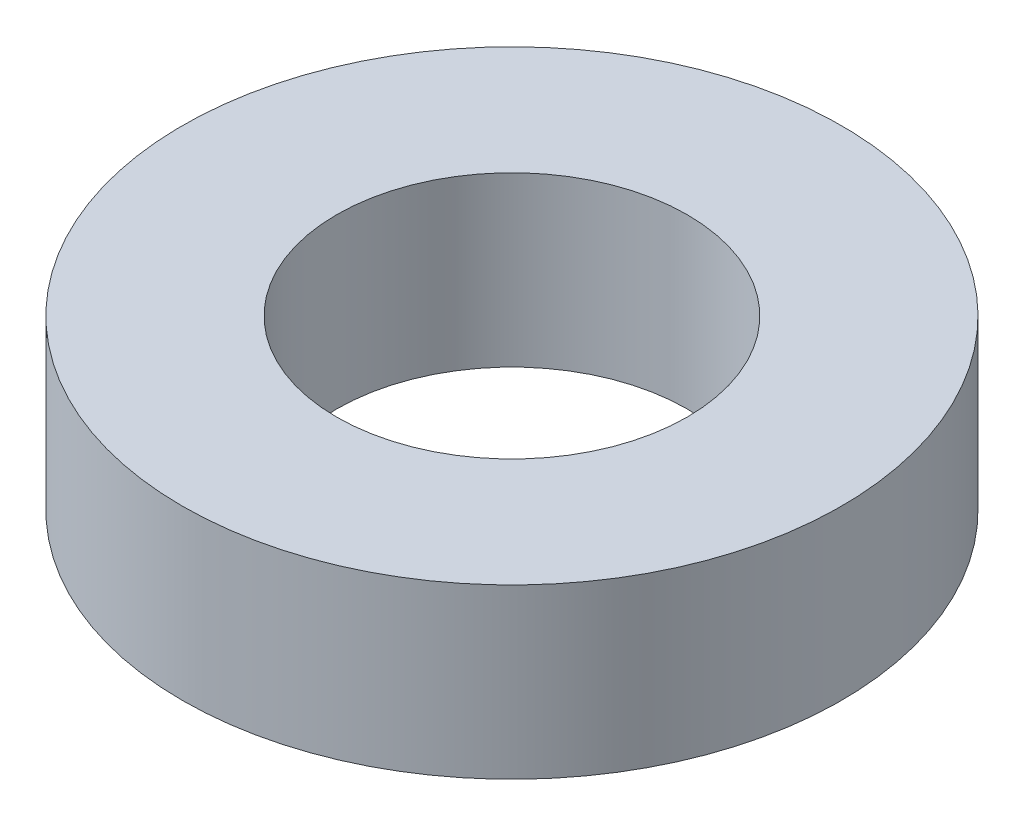
SolidWorks part; units mm, degrees
ref_plane "前视基准面" through (0, 0, 0) normal (0, 0, 1) x (1, 0, 0)
ref_plane "上视基准面" through (0, 0, 0) normal (0, 1, 0) x (1, 0, 0)
ref_plane "右视基准面" through (0, 0, 0) normal (1, 0, 0) x (0, 0, -1)
other "Configuration Table"
sketch "草图1" plane through (0, 0, 0) normal (0, 1, 0) x (1, 0, 0)
  circle A0 centre (0, 0) radius 23.5
  circle A1 centre (0, 0) radius 12.5
  dimension "D1" = 47
  dimension "D2" = 25
extrude "凸台-拉伸1" add sketch "草图1" along normal blind 12
